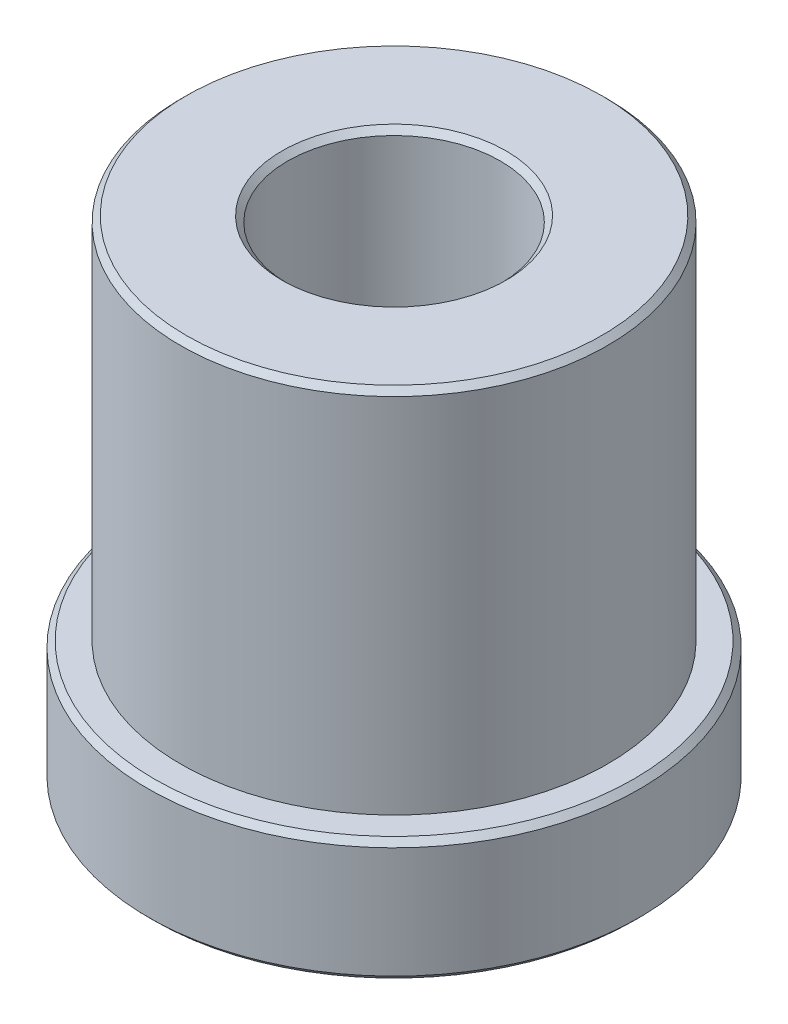
SolidWorks part; units mm, degrees
material "Nylon 101"
ref_plane "Front Plane" through (0, 0, 0) normal (0, 0, 1) x (1, 0, 0)
ref_plane "Top Plane" through (0, 0, 0) normal (0, 1, 0) x (1, 0, 0)
ref_plane "Right Plane" through (0, 0, 0) normal (1, 0, 0) x (0, 0, -1)
sketch "Sketch1" plane through (0, 0, 0) normal (0, 1, 0) x (1, 0, 0)
  circle A0 centre (0, 0) radius 11.049
  dimension "D1" = 22.098
extrude "Boss-Extrude1" add sketch "Sketch1" along normal blind 19.05
sketch "Sketch2" plane through (0, 0, 0) normal (0, -1, 0) x (1, 0, 0)
  circle A0 centre (0, 0) radius 12.7
  dimension "D1" = 25.4
extrude "Boss-Extrude2" add sketch "Sketch2" along normal blind 6.35
sketch "Sketch3" plane through (0, -6.35, 0) normal (0, -1, 0) x (1, 0, 0)
  circle A0 centre (0, 0) radius 5.5
  dimension "D1" = 11
extrude "Cut-Extrude1" cut sketch "Sketch3" against normal through all
sketch "Sketch4" plane through (0, -6.35, 0) normal (0, -1, 0) x (1, 0, 0)
  circle A0 centre (0, 0) radius 11.1125
  dimension "D1" = 22.225
extrude "Cut-Extrude2" cut sketch "Sketch4" against normal blind 5.5372
chamfer "Chamfer1" distance 0.3 angle 45 6 edges at (0, -0.8128, -5.5) (0, 0, -12.7) (0, -6.35, -12.7) (0, -6.35, -11.1125) (0, 19.05, 11.049) (0, 19.05, -5.5)
equation "\"D1@Chamfer1\"=.3mm"
